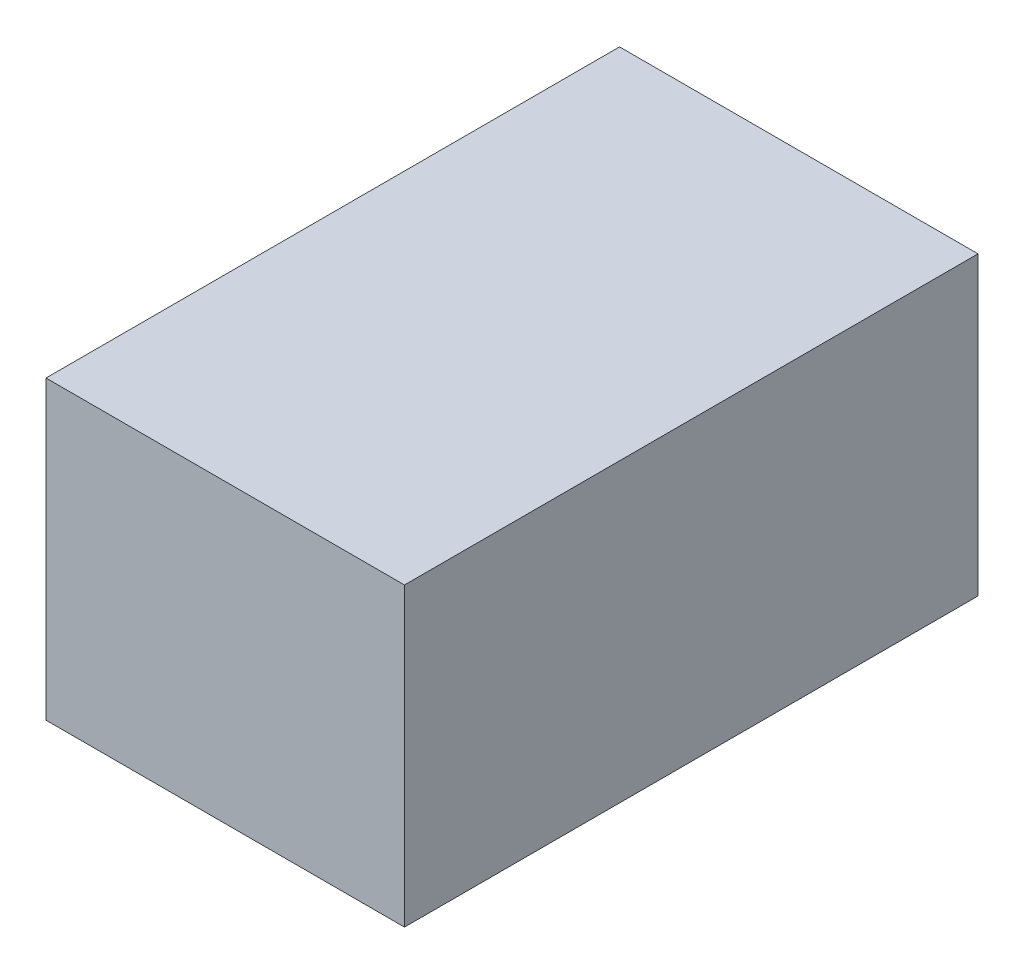
SolidWorks part; units mm, degrees
ref_plane "前视基准面" through (0, 0, 0) normal (0, 0, 1) x (1, 0, 0)
ref_plane "上视基准面" through (0, 0, 0) normal (0, 1, 0) x (1, 0, 0)
ref_plane "右视基准面" through (0, 0, 0) normal (1, 0, 0) x (0, 0, -1)
other "Configuration Table"
sketch "草图2" plane through (0, 0, 0) normal (0, 1, 0) x (1, 0, 0)
  line L1 (-37.5, 60) -> (37.5, 60)
  line L2 (-37.5, 60) -> (-37.5, -60)
  line L3 (-37.5, -60) -> (37.5, -60)
  line L4 (37.5, 60) -> (37.5, -60)
  line L5 (-37.5, 60) -> (37.5, -60) construction
  line L6 (-37.5, -60) -> (37.5, 60) construction
  point P0 (0, 0)
  dimension "D1" = 75
  dimension "D2" = 120
extrude "凸台-拉伸1" add sketch "草图2" along normal blind 62
